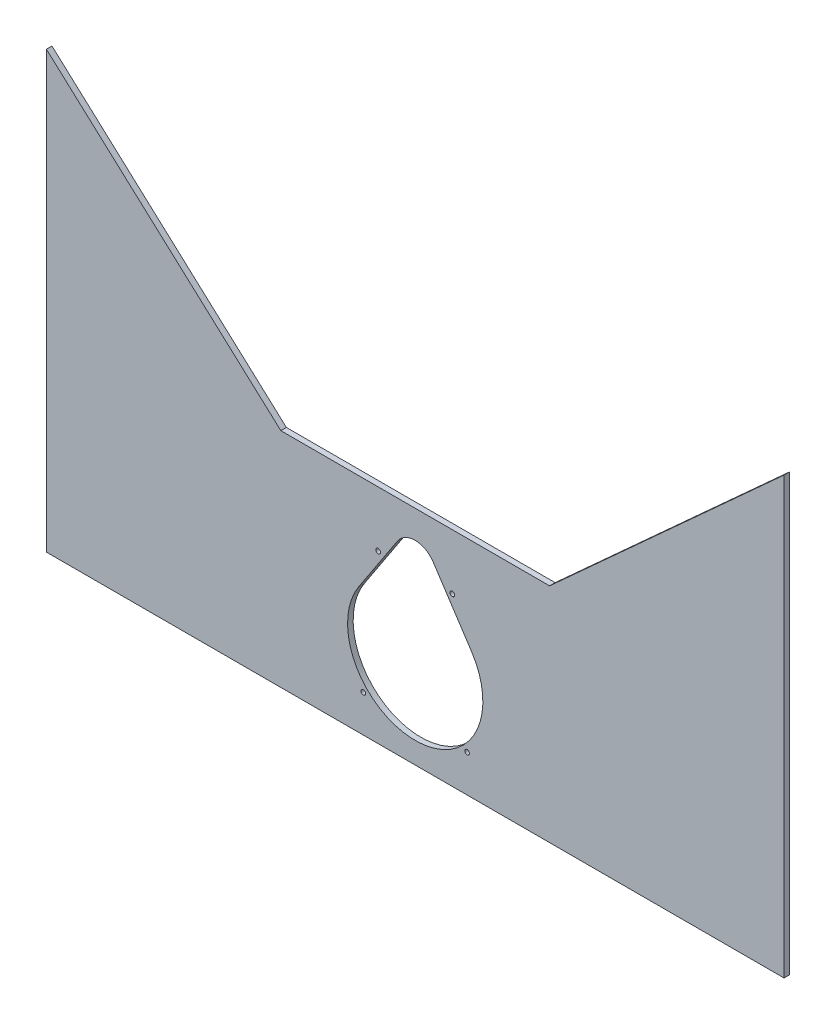
SolidWorks part; units mm, degrees
ref_plane "Front Plane" through (0, 0, 0) normal (0, 0, 1) x (1, 0, 0)
ref_plane "Top Plane" through (0, 0, 0) normal (0, 1, 0) x (1, 0, 0)
ref_plane "Right Plane" through (0, 0, 0) normal (1, 0, 0) x (0, 0, -1)
sketch "Sketch1" plane through (0, 0, 0) normal (0, 0, 1) x (1, 0, 0)
  line L0 (0, 0) -> (398, 0)
  line L1 (398, 0) -> (398, 235)
  line L2 (398, 235) -> (271.5, 120)
  line L3 (271.5, 120) -> (126.5, 120)
  line L4 (126.5, 120) -> (0, 235)
  line L5 (0, 235) -> (0, 0)
  line L6 (199, 20) -> (199, 90) construction
  line L7 (168.5033, 68.0549) -> (189.3914, 99.8187)
  line L8 (208.6086, 99.8187) -> (229.4967, 68.0549)
  circle A0 centre (171, 20) radius 1.25
  circle A1 centre (227, 20) radius 1.25
  circle A2 centre (179, 90) radius 1.25
  circle A3 centre (219, 90) radius 1.25
  arc A4 (168.5033, 68.0549) -> (229.4967, 68.0549) centre (199, 48) ccw
  arc A5 (208.6086, 99.8187) -> (189.3914, 99.8187) centre (199, 93.5) ccw
  point P19 (199, 92)
  dimension "D5" = 2.5
  dimension "D13" = 73
  dimension "D16" = 23
  dimension "D1" = 398
  dimension "D2" = 120
  dimension "D3" = 235
  dimension "D4" = 145
  dimension "D6" = 56
  dimension "D7" = 70
  dimension "D8" = 40
  dimension "D9" = 28
  dimension "D10" = 20
  dimension "D11" = 20
  dimension "D12" = 199
  dimension "D14" = 28
  dimension "D15" = 45.5
extrude "Boss-Extrude1" add sketch "Sketch1" along normal blind 3
